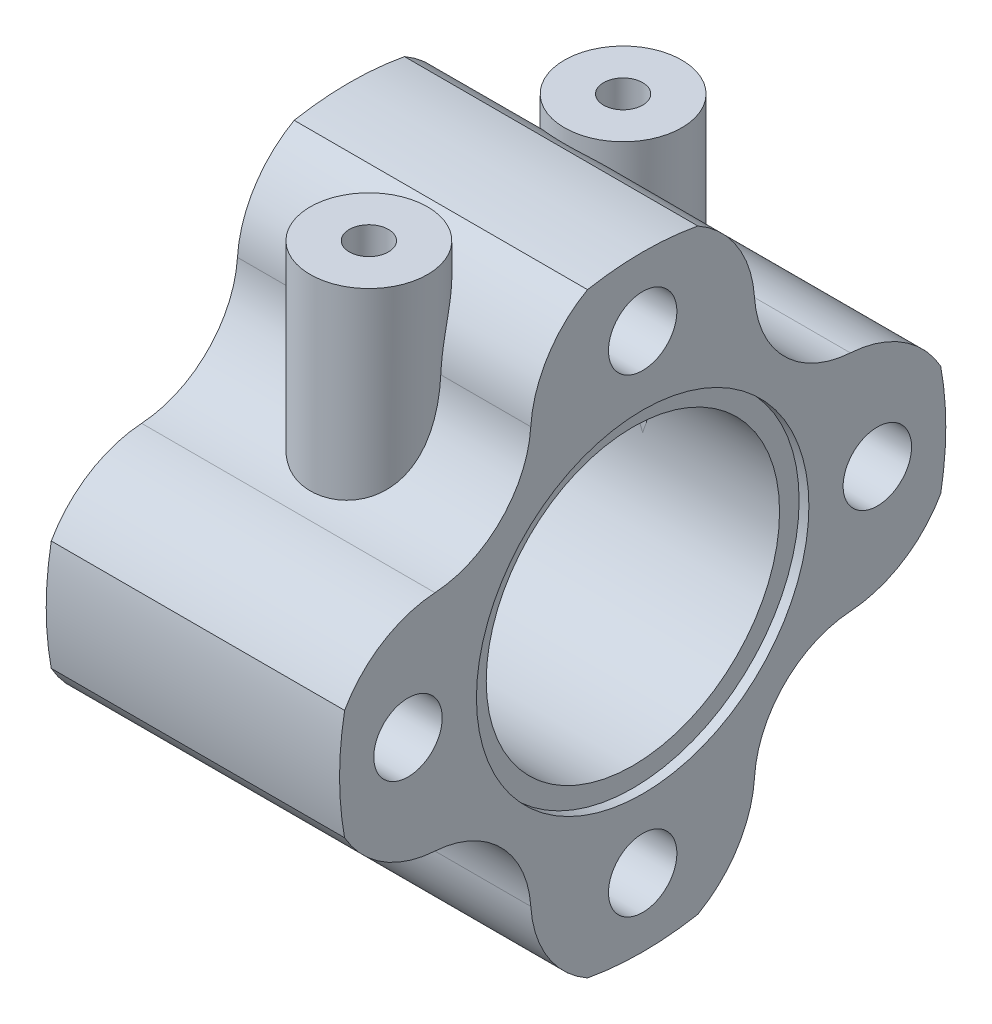
SolidWorks part; units mm, degrees
ref_plane "Front Plane" through (0, 0, 0) normal (0, 0, 1) x (1, 0, 0)
ref_plane "Top Plane" through (0, 0, 0) normal (0, 1, 0) x (1, 0, 0)
ref_plane "Right Plane" through (0, 0, 0) normal (1, 0, 0) x (0, 0, -1)
sketch "Sketch2" plane through (0, 0, 0) normal (1, 0, 0) x (0, 0, -1)
  line L0 (-12, 0) -> (-10.9602, 10.9602) construction
  line L1 (-10.9602, 10.9602) -> (0, 12) construction
  line L2 (0, 55) -> (0, -55) construction
  arc A0 (-15.2412, 2.8209) -> (-15.2412, -2.8209) centre (0, 0) ccw
  circle A1 centre (0, 12) radius 1.75
  circle A2 centre (12, 0) radius 1.75
  circle A3 centre (0, -12) radius 1.75
  circle A4 centre (-12, 0) radius 1.75
  circle A5 centre (0, 0) radius 7.5
  circle A6 centre (0, 0) radius 8.5 construction
  arc A7 (-10.6207, 5.7211) -> (-5.7211, 10.6207) centre (-10.9602, 10.9602) ccw
  circle A8 centre (0, 0) radius 10.25 construction
  arc A9 (-5.7211, 10.6207) -> (-2.8209, 15.2412) centre (0, 10.25) cw
  arc A10 (-2.8209, 15.2412) -> (-6.6728, 13.9901) centre (0, 0) ccw construction
  arc A11 (-5.7336, 11.456) -> (-6.6728, 13.9901) centre (-10.9602, 10.9602) ccw construction
  arc A12 (-6.6728, 13.9901) -> (-10.9602, 10.9602) centre (0, 0) ccw construction
  arc A13 (-10.9602, 10.9602) -> (-13.9901, 6.6728) centre (0, 0) ccw construction
  arc A14 (-5.7211, 10.6207) -> (-5.7336, 11.456) centre (-10.9602, 10.9602) ccw construction
  arc A15 (5.7211, 10.6207) -> (2.8209, 15.2412) centre (0, 10.25) ccw
  arc A16 (5.7211, 10.6207) -> (10.6207, 5.7211) centre (10.9602, 10.9602) ccw
  arc A17 (10.6207, 5.7211) -> (15.2412, 2.8209) centre (10.25, 0) cw
  arc A18 (10.6207, -5.7211) -> (15.2412, -2.8209) centre (10.25, 0) ccw
  arc A19 (10.6207, -5.7211) -> (5.7211, -10.6207) centre (10.9602, -10.9602) ccw
  arc A20 (5.7211, -10.6207) -> (2.8209, -15.2412) centre (0, -10.25) cw
  arc A21 (-5.7211, -10.6207) -> (-2.8209, -15.2412) centre (0, -10.25) ccw
  arc A22 (-5.7211, -10.6207) -> (-10.6207, -5.7211) centre (-10.9602, -10.9602) ccw
  arc A23 (-10.6207, -5.7211) -> (-15.2412, -2.8209) centre (-10.25, 0) cw
  arc A24 (-10.6207, 5.7211) -> (-15.2412, 2.8209) centre (-10.25, 0) ccw
  arc A25 (6.6728, 13.9901) -> (5.7211, 10.6207) centre (10.9602, 10.9602) ccw construction
  arc A26 (13.9901, -6.6728) -> (10.6207, -5.7211) centre (10.9602, -10.9602) ccw construction
  arc A27 (2.8209, -15.2412) -> (13.9901, -6.6728) centre (0, 0) ccw construction
  arc A28 (15.2412, -2.8209) -> (15.2412, 2.8209) centre (0, 0) ccw
  arc A29 (13.9901, -6.6728) -> (15.2412, -2.8209) centre (0, 0) ccw construction
  arc A30 (15.2412, 2.8209) -> (6.6728, 13.9901) centre (0, 0) ccw construction
  arc A31 (2.8209, 15.2412) -> (-2.8209, 15.2412) centre (0, 0) ccw
  arc A32 (-6.6728, -13.9901) -> (-2.8209, -15.2412) centre (0, 0) ccw construction
  arc A33 (-2.8209, -15.2412) -> (2.8209, -15.2412) centre (0, 0) ccw
  arc A34 (-6.6728, -13.9901) -> (-5.7211, -10.6207) centre (-10.9602, -10.9602) ccw construction
  arc A35 (-15.2412, -2.8209) -> (-6.6728, -13.9901) centre (0, 0) ccw construction
  arc A36 (-13.9901, 6.6728) -> (-11.456, 5.7336) centre (-10.9602, 10.9602) ccw construction
  arc A37 (-13.9901, 6.6728) -> (-15.2412, 2.8209) centre (0, 0) ccw construction
  arc A38 (6.6728, 13.9901) -> (2.8209, 15.2412) centre (0, 0) ccw construction
  arc A39 (-11.456, 5.7336) -> (-10.6207, 5.7211) centre (-10.9602, 10.9602) ccw construction
  point P14 (0, 0)
  point P49 (0, 0)
  dimension "D1" = 31
  dimension "D3" = 3.5
  dimension "D5" = 15
  dimension "D6" = 17
  dimension "D7" = 4
  dimension "D4" = 12
  dimension "D2" = 4
extrude "Flange" add sketch "Sketch2" along normal blind 15
sketch "Sketch3" plane through (15, 0, 0) normal (1, 0, 0) x (0, 0, -1)
  circle A0 centre (0, 0) radius 8.5
  dimension "D1" = 17
extrude "O-Ring Seat" cut sketch "Sketch3" against normal blind 0.5
ref_plane "MidPlane Reference" through (7.5, 0, 0) normal (-1, 0, 0) x (0, 0, 1)
mirror "Mirror1" about plane through (7.5, 0, 0) normal (-1, 0, 0) of "O-Ring Seat"
sketch "Sketch5" plane through (0, 0, 0) normal (0, 1, 0) x (1, 0, 0)
  line L0 (7.5, 15.4) -> (7.5, -15.4) construction
  circle A0 centre (7.5, 6.5) radius 1
  dimension "D1" = 2
  dimension "D2" = 6.5
extrude "Outlet" cut sketch "Sketch5" along normal through all
ref_plane "Plane2" through (0, 15.5, 0) normal (0, 1, 0) x (1, 0, 0)
sketch "Sketch6" plane through (0, 15.5, 0) normal (0, 1, 0) x (1, 0, 0)
  circle A2 centre (7.5, 6.5) radius 1
  circle A3 centre (7.5, 6.5) radius 3
  dimension "D1" = 2
extrude "Boss-Extrude2" add sketch "Sketch6" against normal up to next
mirror "Inlet" about plane through (0, 0, 0) normal (0, 0, 1) of "Boss-Extrude2", "Outlet"
